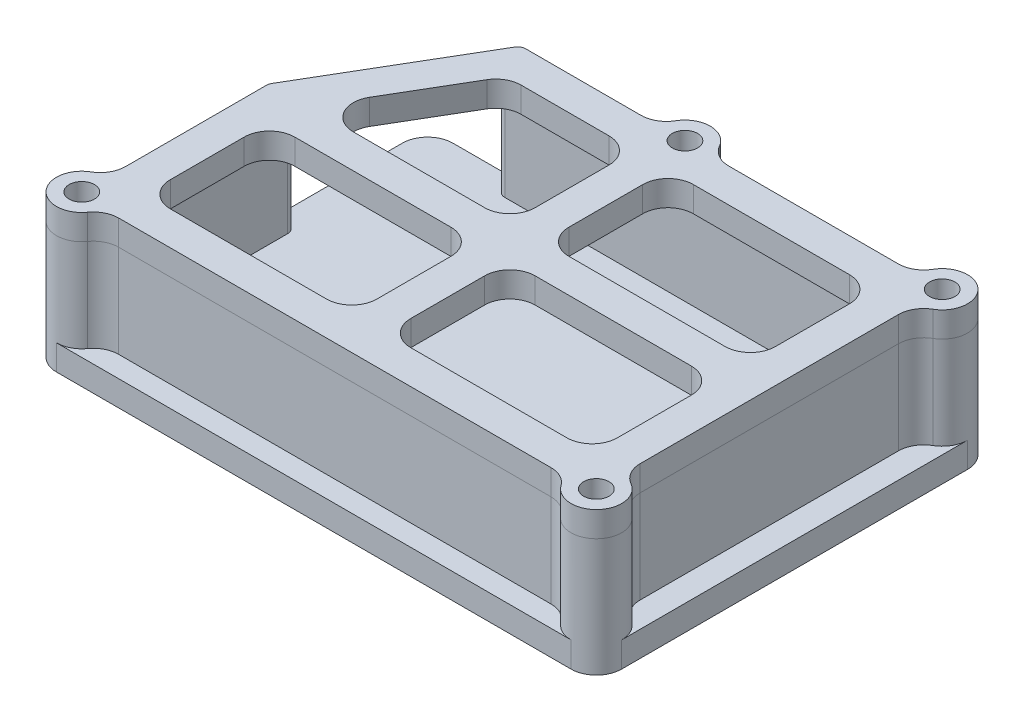
SolidWorks part; units mm, degrees
material "ABS"
ref_plane "Front Plane" through (0, 0, 0) normal (0, 0, 1) x (1, 0, 0)
ref_plane "Top Plane" through (0, 0, 0) normal (0, 1, 0) x (1, 0, 0)
ref_plane "Right Plane" through (0, 0, 0) normal (1, 0, 0) x (0, 0, -1)
sketch "Sketch5" plane through (0, 0, 0) normal (0, 1, 0) x (1, 0, 0)
  line L1 (-28, -18) -> (28, -18) construction
  line L2 (-28, -18) -> (-28, 18) construction
  line L3 (-28, 18) -> (28, 18) construction
  line L4 (28, -18) -> (28, 18) construction
  line L5 (-28, -18) -> (28, 18) construction
  line L6 (-28, 18) -> (28, -18) construction
  line L8 (30.5, -20.5) -> (30.5, 20.5) construction
  line L10 (-5.1962, 20.5) -> (-27.5, 20.5)
  line L14 (-30.5, 17.5) -> (-30.5, -15.3038)
  line L16 (0, 0) -> (0, 20.5) construction
  line L20 (-30.5, 7.9079) -> (-28, 7.9079)
  line L25 (-30.5, -23.5) -> (30.5, -23.5)
  line L26 (33.5, -20.5) -> (33.5, 20.5)
  line L27 (30.5, 23.5) -> (0, 23.5)
  line L28 (-30.5, 20.5) -> (30.5, 20.5) construction
  line L29 (-30.5, -20.5) -> (-30.5, 20.5) construction
  line L30 (-30.5, -20.5) -> (30.5, -20.5) construction
  arc A1 (33.5, 20.5) -> (30.5, 23.5) centre (30.5, 20.5) ccw
  arc A2 (30.5, -23.5) -> (33.5, -20.5) centre (30.5, -20.5) ccw
  arc A3 (-32, -17.9019) -> (-30.5, -23.5) centre (-30.5, -20.5) ccw
  circle A4 centre (0, 20.5) radius 1.5
  circle A5 centre (30.5, 20.5) radius 1.5
  circle A6 centre (30.5, -20.5) radius 1.5
  circle A7 centre (-30.5, -20.5) radius 1.5
  arc A8 (0, 23.5) -> (-2.5981, 22) centre (0, 20.5) ccw
  arc A9 (-27.5, 20.5) -> (-30.5, 17.5) centre (-27.5, 17.5) ccw
  arc A10 (-30.5, -15.3038) -> (-32, -17.9019) centre (-33.5, -15.3038) cw
  arc A11 (-2.5981, 22) -> (-5.1962, 20.5) centre (-5.1962, 23.5) cw
  point P0 (0, 0)
  point P10 (0, 0)
  dimension "D7" = 6
  dimension "D8" = 6
  dimension "D9" = 6
  dimension "D10" = 3
  dimension "D11" = 3
  dimension "D12" = 3
  dimension "D13" = 3
  dimension "D5" = 3
  dimension "D16" = 3
  dimension "D19" = 2.5
  dimension "D1" = 36
  dimension "D2" = 56
  dimension "D4" = 2.5
  dimension "D14" = 2.5
  dimension "D15" = 2.5
  dimension "D17" = 2.5
  dimension "D18" = 2.5
  dimension "D3" = 2.5
extrude "Boss-Extrude2" add sketch "Sketch5" along normal blind 3
sketch "Sketch6" plane through (0, 3, 0) normal (0, 1, 0) x (1, 0, 0)
  line L0 (-30.5, 1.3894) -> (-30.5, -15.3038)
  line L1 (26, 18) -> (-18.8542, 18)
  line L2 (28, 16) -> (28, -16)
  line L3 (26, -18) -> (-26, -18)
  line L4 (-28, 1.3894) -> (-28, -16)
  line L5 (28, 18) -> (-28, -18) construction
  line L6 (28, -18) -> (0, 0) construction
  line L8 (30.5, 15.3038) -> (30.5, -15.3038)
  line L10 (25.3038, 20.5) -> (5.1962, 20.5)
  line L11 (25.6266, -21) -> (-25.6266, -21)
  line L12 (-5.1962, 20.5) -> (-18.8542, 20.5)
  line L13 (-29.5, 2.3894) -> (-29, 2.3894)
  line L14 (-19.8542, 19) -> (-19.8542, 19.5)
  line L15 (-31.9416, 20.5339) -> (-28, 18) construction
  line L16 (-30.5, -23.5) -> (30.5, -23.5) construction
  arc A0 (-5.1962, 20.5) -> (-2.5981, 22) centre (-5.1962, 23.5) ccw construction
  arc A1 (-32, -17.9019) -> (-30.5, -15.3038) centre (-33.5, -15.3038) ccw construction
  arc A2 (-5.1962, 20.5) -> (-2.5981, 22) centre (-5.1962, 23.5) ccw
  arc A3 (-32, -17.9019) -> (-30.5, -15.3038) centre (-33.5, -15.3038) ccw
  arc A4 (-32, -17.9019) -> (-28.0633, -22.25) centre (-30.5, -20.5) ccw
  arc A6 (32, 17.9019) -> (27.9019, 22) centre (30.5, 20.5) ccw
  arc A7 (28.0633, -22.25) -> (32, -17.9019) centre (30.5, -20.5) ccw
  arc A8 (2.5981, 22) -> (-2.5981, 22) centre (0, 20.5) ccw
  circle A9 centre (0, 20.5) radius 1.5
  circle A10 centre (30.5, 20.5) radius 1.5
  circle A11 centre (30.5, -20.5) radius 1.5
  circle A12 centre (-30.5, -20.5) radius 1.5
  circle A13 centre (-30.5, -20.5) radius 1.5 construction
  arc A15 (-25.6266, -21) -> (-28.0633, -22.25) centre (-25.6266, -24) ccw
  arc A16 (30.5, -15.3038) -> (32, -17.9019) centre (33.5, -15.3038) ccw
  arc A17 (25.6266, -21) -> (28.0633, -22.25) centre (25.6266, -24) cw
  arc A18 (32, 17.9019) -> (30.5, 15.3038) centre (33.5, 15.3038) ccw
  arc A19 (27.9019, 22) -> (25.3038, 20.5) centre (25.3038, 23.5) cw
  arc A20 (2.5981, 22) -> (5.1962, 20.5) centre (5.1962, 23.5) ccw
  arc A21 (-26, -18) -> (-28, -16) centre (-26, -16) cw
  arc A22 (28, -16) -> (26, -18) centre (26, -16) cw
  arc A23 (26, 18) -> (28, 16) centre (26, 16) cw
  arc A25 (-19.8542, 19.5) -> (-18.8542, 20.5) centre (-18.8542, 19.5) cw
  arc A26 (-19.8542, 19) -> (-18.8542, 18) centre (-18.8542, 19) ccw
  arc A27 (-29, 2.3894) -> (-28, 1.3894) centre (-29, 1.3894) cw
  arc A28 (-29.5, 2.3894) -> (-30.5, 1.3894) centre (-29.5, 1.3894) ccw
  circle A29 centre (0, 20.5) radius 1.5 construction
  point P0 (0, 0)
  dimension "D3" = 3
  dimension "D4" = 2
  dimension "D5" = 1
  dimension "D6" = 3
  dimension "D8" = 3
  dimension "D1" = 36
  dimension "D2" = 56
  dimension "D7" = 2.5
  dimension "D9" = 2.5
  dimension "D10" = 2.5
extrude "Boss-Extrude3" add sketch "Sketch6" along normal blind 11
sketch "Sketch7" plane through (0, 14, 0) normal (0, 1, 0) x (1, 0, 0)
  line L1 (-30.3621, 1.8962) -> (-19.7162, 20.0068)
  line L2 (-26.5, -14) -> (-26.5, -5.25)
  line L3 (-23.151, 6.2703) -> (-18.0075, 15.0203)
  line L4 (-15.4213, 16.5) -> (-5, 16.5)
  line L5 (26.5, 13.5) -> (26.5, 4.75)
  line L6 (23.5, -17) -> (5, -17)
  line L7 (-5, 1.75) -> (-20.5647, 1.75)
  line L8 (-5, -2.25) -> (-23.5, -2.25)
  line L9 (2, -14) -> (2, -5.25)
  line L10 (23.5, 1.75) -> (5, 1.75)
  line L11 (-25.6266, -21) -> (25.6266, -21)
  line L12 (30.5, -15.3038) -> (30.5, 15.3038)
  line L13 (25.3038, 20.5) -> (5.1962, 20.5)
  line L14 (-5.1962, 20.5) -> (-18.8542, 20.5)
  line L15 (-19.8542, 19.5) -> (-19.8542, 19)
  line L16 (-18.8542, 18) -> (26, 18)
  line L17 (28, 16) -> (28, -16)
  line L18 (26, -18) -> (-26, -18)
  line L19 (-28, -16) -> (-28, 1.3894)
  line L20 (-29, 2.3894) -> (-29.5, 2.3894)
  line L21 (-30.5, 1.3894) -> (-30.5, -15.3038)
  line L22 (-25.6266, -21) -> (25.6266, -21)
  line L23 (30.5, -15.3038) -> (30.5, 15.3038)
  line L24 (25.3038, 20.5) -> (5.1962, 20.5)
  line L25 (-5.1962, 20.5) -> (-18.8542, 20.5)
  line L32 (-30.5, 1.3894) -> (-30.5, -15.3038)
  line L33 (-2, -14) -> (-2, -5.25)
  line L34 (23.5, -2.25) -> (5, -2.25)
  line L35 (5, 16.5) -> (23.5, 16.5)
  line L36 (-5, -17) -> (-23.5, -17)
  line L37 (-2, 4.75) -> (-2, 13.5)
  line L41 (2, 4.75) -> (2, 13.5)
  line L43 (26.5, -5.25) -> (26.5, -14)
  arc A0 (-18.8542, 20.5) -> (-19.8542, 19.5) centre (-18.8542, 19.5) ccw construction
  arc A1 (-29.5, 2.3894) -> (-30.5, 1.3894) centre (-29.5, 1.3894) ccw construction
  arc A2 (-18.8542, 20.5) -> (-19.7162, 20.0068) centre (-18.8542, 19.5) ccw
  arc A3 (-30.3621, 1.8962) -> (-30.5, 1.3894) centre (-29.5, 1.3894) ccw
  arc A4 (2, -5.25) -> (5, -2.25) centre (5, -5.25) cw
  arc A5 (2, -14) -> (5, -17) centre (5, -14) ccw
  arc A6 (26.5, -14) -> (23.5, -17) centre (23.5, -14) cw
  arc A7 (23.5, -2.25) -> (26.5, -5.25) centre (23.5, -5.25) cw
  arc A8 (23.5, 1.75) -> (26.5, 4.75) centre (23.5, 4.75) ccw
  arc A9 (23.5, 16.5) -> (26.5, 13.5) centre (23.5, 13.5) cw
  arc A10 (2, 4.75) -> (5, 1.75) centre (5, 4.75) ccw
  arc A11 (5, 16.5) -> (2, 13.5) centre (5, 13.5) ccw
  arc A12 (-18.0075, 15.0203) -> (-15.4213, 16.5) centre (-15.4213, 13.5) cw
  arc A13 (-5, 16.5) -> (-2, 13.5) centre (-5, 13.5) cw
  arc A14 (-2, 4.75) -> (-5, 1.75) centre (-5, 4.75) cw
  arc A15 (-2, -5.25) -> (-5, -2.25) centre (-5, -5.25) ccw
  arc A16 (-2, -14) -> (-5, -17) centre (-5, -14) cw
  arc A17 (-26.5, -14) -> (-23.5, -17) centre (-23.5, -14) ccw
  arc A18 (-23.5, -2.25) -> (-26.5, -5.25) centre (-23.5, -5.25) ccw
  arc A19 (-25.6266, -21) -> (-28.0633, -22.25) centre (-25.6266, -24) ccw
  arc A20 (28.0633, -22.25) -> (25.6266, -21) centre (25.6266, -24) ccw
  arc A21 (28.0633, -22.25) -> (32, -17.9019) centre (30.5, -20.5) ccw
  arc A22 (30.5, -15.3038) -> (32, -17.9019) centre (33.5, -15.3038) ccw
  arc A23 (32, 17.9019) -> (30.5, 15.3038) centre (33.5, 15.3038) ccw
  arc A24 (32, 17.9019) -> (27.9019, 22) centre (30.5, 20.5) ccw
  arc A25 (25.3038, 20.5) -> (27.9019, 22) centre (25.3038, 23.5) ccw
  arc A26 (2.5981, 22) -> (5.1962, 20.5) centre (5.1962, 23.5) ccw
  arc A27 (2.5981, 22) -> (-2.5981, 22) centre (0, 20.5) ccw
  arc A28 (-5.1962, 20.5) -> (-2.5981, 22) centre (-5.1962, 23.5) ccw
  arc A29 (-18.8542, 20.5) -> (-19.8542, 19.5) centre (-18.8542, 19.5) ccw
  arc A30 (-19.8542, 19) -> (-18.8542, 18) centre (-18.8542, 19) ccw
  arc A31 (28, 16) -> (26, 18) centre (26, 16) ccw
  arc A32 (26, -18) -> (28, -16) centre (26, -16) ccw
  arc A33 (-28, -16) -> (-26, -18) centre (-26, -16) ccw
  arc A34 (-28, 1.3894) -> (-29, 2.3894) centre (-29, 1.3894) ccw
  arc A35 (-29.5, 2.3894) -> (-30.5, 1.3894) centre (-29.5, 1.3894) ccw
  arc A36 (-32, -17.9019) -> (-30.5, -15.3038) centre (-33.5, -15.3038) ccw
  arc A37 (-32, -17.9019) -> (-28.0633, -22.25) centre (-30.5, -20.5) ccw
  arc A38 (-25.6266, -21) -> (-28.0633, -22.25) centre (-25.6266, -24) ccw
  arc A39 (28.0633, -22.25) -> (25.6266, -21) centre (25.6266, -24) ccw
  arc A40 (28.0633, -22.25) -> (32, -17.9019) centre (30.5, -20.5) ccw
  arc A41 (30.5, -15.3038) -> (32, -17.9019) centre (33.5, -15.3038) ccw
  arc A42 (32, 17.9019) -> (30.5, 15.3038) centre (33.5, 15.3038) ccw
  arc A43 (32, 17.9019) -> (27.9019, 22) centre (30.5, 20.5) ccw
  arc A44 (25.3038, 20.5) -> (27.9019, 22) centre (25.3038, 23.5) ccw
  arc A45 (2.5981, 22) -> (5.1962, 20.5) centre (5.1962, 23.5) ccw
  arc A46 (2.5981, 22) -> (-2.5981, 22) centre (0, 20.5) ccw
  arc A47 (-5.1962, 20.5) -> (-2.5981, 22) centre (-5.1962, 23.5) ccw
  arc A55 (-32, -17.9019) -> (-30.5, -15.3038) centre (-33.5, -15.3038) ccw
  arc A56 (-32, -17.9019) -> (-28.0633, -22.25) centre (-30.5, -20.5) ccw
  arc A57 (-20.5647, 1.75) -> (-23.151, 6.2703) centre (-20.5647, 4.75) cw
  circle A58 centre (0, 20.5) radius 1.5 construction
  circle A59 centre (30.5, 20.5) radius 1.5 construction
  circle A60 centre (30.5, -20.5) radius 1.5 construction
  circle A61 centre (-30.5, -20.5) radius 1.5 construction
  circle A62 centre (0, 20.5) radius 1.5
  circle A63 centre (30.5, 20.5) radius 1.5
  circle A64 centre (30.5, -20.5) radius 1.5
  circle A65 centre (-30.5, -20.5) radius 1.5
  point P93 (-2, 1.75)
  point P96 (-2, -2.25)
  dimension "D7" = 3
  dimension "D2" = 4
  dimension "D3" = 4
  dimension "D4" = 4
  dimension "D5" = 4
  dimension "D6" = 4
  dimension "D1" = 0
extrude "Boss-Extrude4" add sketch "Sketch7" along normal blind 3 separate body
